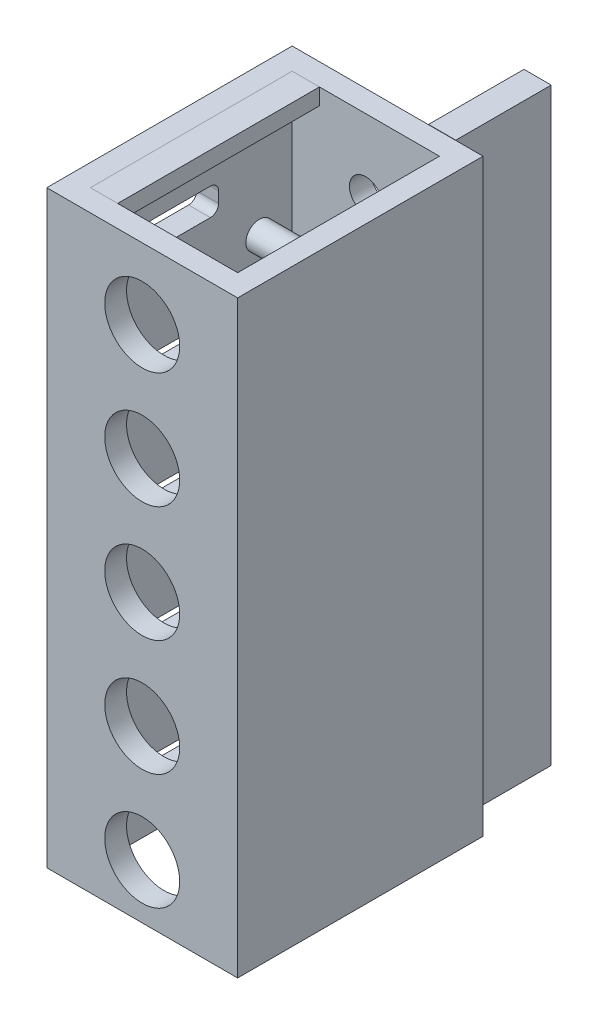
SolidWorks part; units mm, degrees
ref_plane "Front Plane" through (0, 0, 0) normal (0, 0, 1) x (1, 0, 0)
ref_plane "Top Plane" through (0, 0, 0) normal (0, 1, 0) x (1, 0, 0)
ref_plane "Right Plane" through (0, 0, 0) normal (1, 0, 0) x (0, 0, -1)
sketch "Sketch1" plane through (0, 0, 0) normal (0, 0, 1) x (1, 0, 0)
  line L4 (20.8043, 109.7578) -> (20.8043, -28.4094) construction
  line L37 (-74.1395, 84.3934) -> (80.8605, 84.3934)
  line L41 (80.8605, 84.3934) -> (135.8605, -95.6066)
  line L42 (135.8605, -95.6066) -> (-74.1395, -95.6066)
  line L44 (-74.1395, -95.6066) -> (-74.1395, 84.3934)
  circle A0 centre (-42.1957, 67.1864) radius 5
  circle A1 centre (-42.1957, 47.1864) radius 5
  circle A2 centre (-42.1957, 27.1864) radius 5
  circle A3 centre (-42.1957, 7.1864) radius 5
  circle A4 centre (-42.1957, -12.8136) radius 5
  circle A5 centre (0.8043, 63.6864) radius 5
  circle A6 centre (0.8043, 38.1864) radius 5
  circle A7 centre (0.8043, 12.6864) radius 5
  circle A8 centre (0.8043, -10.3136) radius 5
  circle A11 centre (40.8043, -10.3136) radius 5
  circle A12 centre (40.8043, 12.6864) radius 5
  circle A13 centre (40.8043, 38.1864) radius 5
  circle A14 centre (40.8043, 63.6864) radius 5
  circle A15 centre (-40.6957, -37.8136) radius 5
  circle A16 centre (1.3043, -37.8136) radius 5
  circle A17 centre (43.3043, -37.8136) radius 5
  circle A18 centre (-39.1957, -75.8136) radius 5
  circle A19 centre (-19.1957, -75.8136) radius 5
  circle A20 centre (0.8043, -75.8136) radius 5
  circle A21 centre (20.8043, -75.8136) radius 5
  circle A22 centre (40.8043, -75.8136) radius 5
  circle A23 centre (80.8043, -72.8136) radius 5
sketch "Sketch2" plane through (0, 0, 0) normal (0, 0, 1) x (1, 0, 0)
  line L0 (-74.1395, -95.6066) -> (-74.1395, 84.3934) construction
  line L1 (-29.1395, 79.3934) -> (-64.1395, 79.3934)
  line L2 (-29.1395, 79.3934) -> (-29.1395, -25.6066)
  line L3 (-29.1395, -25.6066) -> (-64.1395, -25.6066)
  line L4 (-64.1395, 79.3934) -> (-64.1395, -25.6066)
  line L5 (-74.1395, 84.3934) -> (80.8605, 84.3934) construction
  line L6 (135.8605, -95.6066) -> (-74.1395, -95.6066) construction
  dimension "D1" = 35
  dimension "D2" = 10
  dimension "D3" = 5
  dimension "D4" = 70
extrude "Boss-Extrude1" add sketch "Sketch2" against normal blind 45
sketch "Sketch3" plane through (0, 79.3934, 0) normal (0, 1, 0) x (1, 0, 0)
  line L0 (-29.1395, 45) -> (-64.1395, 45) construction
  line L1 (-60.1395, 41) -> (-33.1395, 41)
  line L2 (-60.1395, 41) -> (-60.1395, 4)
  line L3 (-60.1395, 4) -> (-33.1395, 4)
  line L4 (-33.1395, 41) -> (-33.1395, 4)
  line L5 (-64.1395, 45) -> (-64.1395, 0) construction
  line L6 (-44.1957, 0) -> (-34.1957, 0) construction
  line L7 (-29.1395, 45) -> (-29.1395, 0) construction
  dimension "D1" = 4
  dimension "D2" = 4
  dimension "D3" = 4
  dimension "D4" = 4
extrude "Cut-Extrude1" cut sketch "Sketch3" against normal up to next
sketch "Sketch4" plane through (0, 0, 0) normal (0, 0, 1) x (1, 0, 0)
  line L0 (-64.1395, -25.6066) -> (-29.1395, -25.6066) construction
  line L1 (-64.1395, 79.3934) -> (-64.1395, -25.6066) construction
  circle A0 centre (-46.6395, 69.3934) radius 6.875
  circle A1 centre (-46.6395, 48.1434) radius 6.875
  circle A2 centre (-46.6395, 26.8934) radius 6.875
  circle A4 centre (-46.6395, 5.6434) radius 6.875
  circle A5 centre (-46.6395, -15.6066) radius 6.875
  dimension "D1" = 13.75
  dimension "D2" = 13.75
  dimension "D3" = 13.75
  dimension "D4" = 13.75
  dimension "D5" = 13.75
  dimension "D6" = 21.25
  dimension "D7" = 21.25
  dimension "D8" = 21.25
  dimension "D9" = 21.25
  dimension "D10" = 10
  dimension "D11" = 17.5
extrude "Cut-Extrude2" cut sketch "Sketch4" against normal blind 10
sketch "Sketch12" plane through (-29.1395, 0, 0) normal (1, 0, 0) x (0, 0, -1)
  line L0 (0, -25.6066) -> (0, 79.3934) construction
  line L1 (9, 7.8934) -> (26, 7.8934)
  line L2 (7.5, 6.3934) -> (7.5, 4.3934)
  line L3 (9, 2.8934) -> (26, 2.8934)
  line L4 (27.5, 6.3934) -> (27.5, 4.3934)
  line L5 (9, 29.1434) -> (26, 29.1434)
  line L6 (7.5, 27.6434) -> (7.5, 25.6434)
  line L7 (9, 24.1434) -> (26, 24.1434)
  line L8 (27.5, 27.6434) -> (27.5, 25.6434)
  line L9 (9, 50.3934) -> (26, 50.3934)
  line L10 (7.5, 48.8934) -> (7.5, 46.8934)
  line L11 (9, 45.3934) -> (26, 45.3934)
  line L12 (27.5, 48.8934) -> (27.5, 46.8934)
  line L13 (9, 71.6434) -> (26, 71.6434)
  line L14 (7.5, 70.1434) -> (7.5, 68.1434)
  line L15 (9, 66.6434) -> (26, 66.6434)
  line L16 (27.5, 70.1434) -> (27.5, 68.1434)
  line L17 (9, -13.3566) -> (26, -13.3566)
  line L18 (7.5, -14.8566) -> (7.5, -16.8566)
  line L19 (9, -18.3566) -> (26, -18.3566)
  line L20 (27.5, -14.8566) -> (27.5, -16.8566)
  line L22 (45, -25.6066) -> (0, -25.6066) construction
  line L23 (0, -95.6066) -> (0, 84.3934) construction
  arc A0 (26, -13.3566) -> (27.5, -14.8566) centre (26, -14.8566) cw
  arc A1 (27.5, -16.8566) -> (26, -18.3566) centre (26, -16.8566) cw
  arc A2 (9, -18.3566) -> (7.5, -16.8566) centre (9, -16.8566) cw
  arc A3 (7.5, -14.8566) -> (9, -13.3566) centre (9, -14.8566) cw
  arc A4 (26, 7.8934) -> (27.5, 6.3934) centre (26, 6.3934) cw
  arc A5 (27.5, 4.3934) -> (26, 2.8934) centre (26, 4.3934) cw
  arc A6 (9, 2.8934) -> (7.5, 4.3934) centre (9, 4.3934) cw
  arc A7 (7.5, 6.3934) -> (9, 7.8934) centre (9, 6.3934) cw
  arc A8 (26, 29.1434) -> (27.5, 27.6434) centre (26, 27.6434) cw
  arc A9 (27.5, 25.6434) -> (26, 24.1434) centre (26, 25.6434) cw
  arc A10 (9, 24.1434) -> (7.5, 25.6434) centre (9, 25.6434) cw
  arc A11 (7.5, 27.6434) -> (9, 29.1434) centre (9, 27.6434) cw
  arc A12 (26, 50.3934) -> (27.5, 48.8934) centre (26, 48.8934) cw
  arc A13 (27.5, 46.8934) -> (26, 45.3934) centre (26, 46.8934) cw
  arc A14 (9, 45.3934) -> (7.5, 46.8934) centre (9, 46.8934) cw
  arc A15 (7.5, 48.8934) -> (9, 50.3934) centre (9, 48.8934) cw
  arc A16 (26, 66.6434) -> (27.5, 68.1434) centre (26, 68.1434) ccw
  arc A17 (27.5, 70.1434) -> (26, 71.6434) centre (26, 70.1434) ccw
  arc A18 (9, 66.6434) -> (7.5, 68.1434) centre (9, 68.1434) cw
  arc A19 (7.5, 70.1434) -> (9, 71.6434) centre (9, 70.1434) cw
  point P30 (27.5, -18.3566)
  point P33 (7.5, -18.3566)
  point P36 (7.5, -13.3566)
  point P39 (27.5, 7.8934)
  point P44 (7.5, 2.8934)
  point P47 (7.5, 7.8934)
  point P50 (27.5, 29.1434)
  point P55 (7.5, 24.1434)
  point P58 (7.5, 29.1434)
  point P61 (27.5, 50.3934)
  point P66 (7.5, 45.3934)
  point P69 (7.5, 50.3934)
  point P74 (27.5, 71.6434)
  point P77 (7.5, 66.6434)
  point P80 (7.5, 71.6434)
  dimension "D21" = 1.5
  dimension "D1" = 5
  dimension "D2" = 20
  dimension "D3" = 7.5
  dimension "D4" = 7.25
  dimension "D5" = 16.25
  dimension "D6" = 5
  dimension "D7" = 20
  dimension "D8" = 7.5
  dimension "D9" = 5
  dimension "D10" = 20
  dimension "D11" = 7.5
  dimension "D12" = 16.25
  dimension "D13" = 16.25
  dimension "D14" = 16.25
  dimension "D15" = 5
  dimension "D16" = 5
  dimension "D17" = 7.5
  dimension "D18" = 7.5
  dimension "D19" = 20
  dimension "D20" = 20
sketch "Sketch14" plane through (-60.1395, 0, 0) normal (1, 0, 0) x (0, 0, -1)
  line L2 (41, 79.3934) -> (4, 79.3934) construction
  line L3 (41, -25.6066) -> (41, 79.3934) construction
  circle A0 centre (35, 59.3934) radius 2.5
  dimension "D1" = 5
  dimension "D2" = 20
  dimension "D3" = 6
extrude "Boss-Extrude2" add sketch "Sketch14" along normal blind 10 contours A0
sketch "Sketch15" plane through (-50.1395, 0, 0) normal (1, 0, 0) x (0, 0, -1)
  circle A0 centre (35, 59.3934) radius 2.5
  circle A1 centre (35, 59.3934) radius 1.75
  dimension "D1" = 3.5
extrude "Cut-Extrude7" cut sketch "Sketch15" against normal blind 1.5 from offset 2 offset against normal yes
sketch "Sketch16" plane through (-60.1395, 0, 0) normal (1, 0, 0) x (0, 0, -1)
  line L5 (41, -25.6066) -> (41, 79.3934) construction
  line L6 (41, 79.3934) -> (4, 79.3934)
  line L7 (41, 79.3934) -> (41, 82.3934)
  line L8 (41, 82.3934) -> (4, 82.3934)
  line L9 (4, 79.3934) -> (4, 82.3934)
  line L10 (4, -25.6066) -> (4, 79.3934) construction
  line L11 (41, 79.3934) -> (4, 79.3934) construction
  dimension "D1" = 0
  dimension "D2" = 0
  dimension "D3" = 3
extrude "Boss-Extrude4" add sketch "Sketch16" along normal blind 5
sketch "Sketch17" plane through (0, 79.3934, 0) normal (0, 1, 0) x (1, 0, 0)
  line L10 (-29.1395, 0) -> (-64.1395, 0)
  line L11 (-29.1395, 0) -> (-29.1395, 45)
  line L12 (-29.1395, 45) -> (-64.1395, 45)
  line L13 (-64.1395, 0) -> (-64.1395, 45)
  line L14 (-33.1395, 4) -> (-60.1395, 4)
  line L15 (-33.1395, 4) -> (-33.1395, 41)
  line L16 (-33.1395, 41) -> (-60.1395, 41)
  line L17 (-60.1395, 4) -> (-60.1395, 41)
extrude "Boss-Extrude5" add sketch "Sketch17" along normal blind 3
sketch "Sketch18" plane through (0, 0, -41) normal (0, 0, 1) x (1, 0, 0)
  circle A0 centre (-46.6395, 69.3934) radius 3
  circle A1 centre (-46.6395, 48.1434) radius 3
  circle A2 centre (-46.6395, 26.8934) radius 3
  circle A3 centre (-46.6395, 5.6434) radius 3
  circle A4 centre (-46.6395, -15.6066) radius 3
  dimension "D1" = 6
  dimension "D2" = 6
  dimension "D3" = 6
  dimension "D4" = 6
  dimension "D5" = 6
extrude "Cut-Extrude8" cut sketch "Sketch18" against normal blind 10
sketch "Sketch19" plane through (0, 0, -45) normal (0, 0, -1) x (-1, 0, 0)
  line L0 (64.1395, -25.6066) -> (29.1395, -25.6066) construction
  line L1 (34.1395, 82.4401) -> (39.1395, 82.4401)
  line L2 (34.1395, 82.4401) -> (34.1395, -25.6066)
  line L3 (34.1395, -25.6066) -> (39.1395, -25.6066)
  line L4 (39.1395, 82.4401) -> (39.1395, -25.6066)
  line L5 (29.1395, -25.6066) -> (29.1395, 82.3934) construction
  point P7 (0, 0)
  dimension "D1" = 5
  dimension "D2" = 5
extrude "Cut-Extrude9" cut sketch "Sketch12" against normal blind 10 from offset 30 offset against normal yes
extrude "Boss-Extrude6" add sketch "Sketch19" along normal blind 17.5
